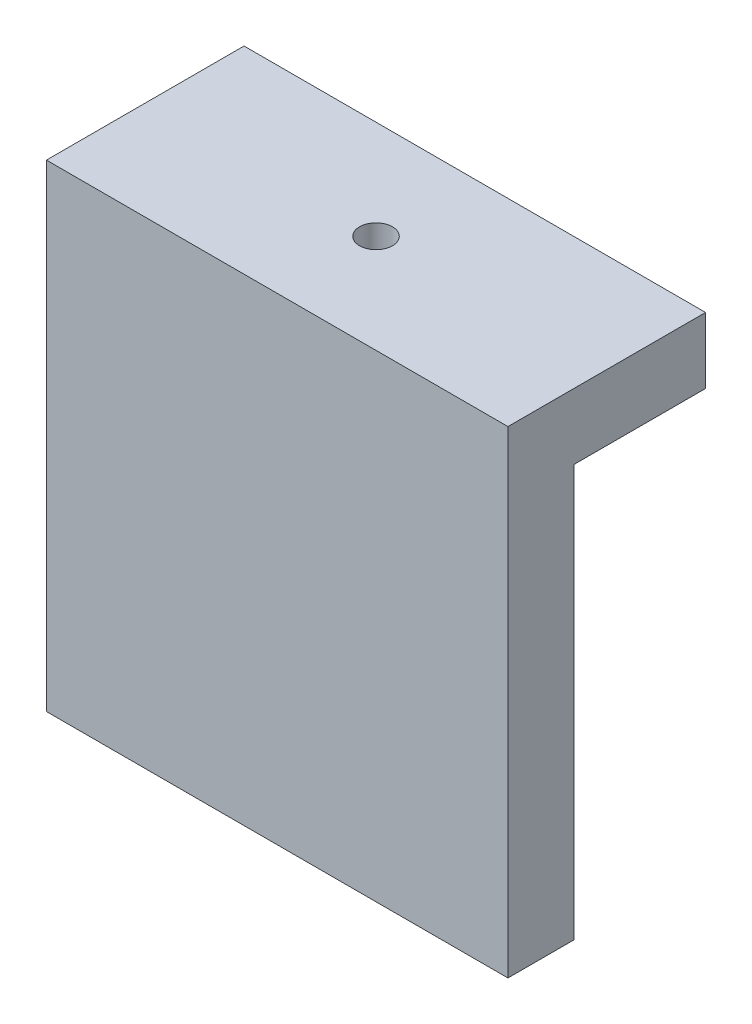
SolidWorks part; units mm, degrees
ref_plane "Front Plane" through (0, 0, 0) normal (0, 0, 1) x (1, 0, 0)
ref_plane "Top Plane" through (0, 0, 0) normal (0, 1, 0) x (1, 0, 0)
ref_plane "Right Plane" through (0, 0, 0) normal (1, 0, 0) x (0, 0, -1)
sketch "Sketch1" plane through (0, 0, 0) normal (0, 0, 1) x (1, 0, 0)
  line L1 (20.025, -25) -> (-20.025, -25)
  line L2 (20.025, -25) -> (20.025, 25)
  line L3 (20.025, 25) -> (-20.025, 25)
  line L4 (-20.025, -25) -> (-20.025, 25)
  line L5 (20.025, -25) -> (-20.025, 25) construction
  line L6 (20.025, 25) -> (-20.025, -25) construction
  point P0 (0, 0)
  dimension "D1" = 40.05
  dimension "D2" = 50
extrude "Boss-Extrude1" add sketch "Sketch1" along normal mid plane 8
sketch "Sketch2" plane through (20.025, 0, 0) normal (1, 0, 0) x (0, 0, -1)
  line L0 (-4, -25) -> (-4, 33)
  line L1 (-4, 33) -> (20, 33)
  line L2 (20, 33) -> (20, -25)
  line L3 (20, -25) -> (-4, -25)
  line L4 (4, -25) -> (4, 25) construction
  line L5 (-4, 25) -> (4, 25) construction
  dimension "D1" = 16
  dimension "D2" = 8
extrude "Boss-Extrude2" add sketch "Sketch2" along normal blind 8
sketch "Sketch4" plane through (-20.025, 0, 0) normal (-1, 0, 0) x (0, 0, 1)
  line L0 (4, -25) -> (-20, -25)
  line L1 (-20, -25) -> (-20, 33)
  line L2 (4, -25) -> (4, 33)
  line L3 (4, 33) -> (-20, 33)
  line L4 (-4, 25) -> (-4, -25) construction
  line L5 (4, 25) -> (-4, 25) construction
  dimension "D1" = 16
  dimension "D2" = 8
extrude "Boss-Extrude3" add sketch "Sketch4" along normal blind 8
sketch "Sketch5" plane through (20.025, 0, 0) normal (-1, 0, 0) x (0, 0, 1)
  line L0 (-20, -25) -> (-20, 33)
  line L1 (-20, 33) -> (4, 33)
  line L2 (4, 33) -> (4, 25)
  line L3 (4, 25) -> (-12.05, 25)
  line L4 (-12.05, 25) -> (-12.05, -25)
  line L5 (-4, -25) -> (-20, -25) construction
  line L6 (-12.05, -25) -> (-20, -25)
  dimension "D1" = 7.95
extrude "Boss-Extrude5" add sketch "Sketch5" along normal up to surface (40.05 mm away) from surface at 0 contours L6 L0 L1 L2 L3 L4 up to face at (-20.025, 11, -6.6667) starting at face at (20.025, 11, -6.6667)
sketch "Sketch6" plane through (0, 0, -20) normal (0, 0, -1) x (-1, 0, 0)
  line L0 (-16.025, -25) -> (-16.025, 25)
  line L1 (-28.025, -25) -> (28.025, -25) construction
  line L2 (-16.025, 25) -> (16.025, 25)
  line L3 (16.025, 25) -> (16.025, -25)
  line L4 (-28.025, -25) -> (-28.025, 33) construction
  line L5 (28.025, 33) -> (28.025, -25) construction
  line L6 (16.025, -25) -> (-16.025, -25)
  dimension "D1" = 12
  dimension "D2" = 12
  dimension "D3" = 50
extrude "Cut-Extrude1" cut sketch "Sketch6" against normal blind 8
sketch "Sketch7" plane through (0, 33, 0) normal (0, 1, 0) x (1, 0, 0)
  line L0 (28.025, 8) -> (-28.025, 8) construction
  line L1 (28.025, 20) -> (28.025, -4) construction
  line L2 (-28.025, -4) -> (-28.025, 20) construction
  line L3 (0, 20) -> (0, -4) construction
  line L4 (28.025, 20) -> (-28.025, 20) construction
  line L5 (28.025, -4) -> (-28.025, -4) construction
  circle A0 centre (0, 8) radius 2
  dimension "D1" = 4
extrude "Cut-Extrude2" cut sketch "Sketch7" against normal blind 8
sketch "Sketch9" plane through (20.025, 0, 0) normal (-1, 0, 0) x (0, 0, 1)
  line L0 (-8.025, -25) -> (-8.025, 25) construction
  line L1 (-4, -25) -> (-12.05, -25) construction
  line L2 (-12.05, 25) -> (-4, 25) construction
  line L4 (-4, -25) -> (-4, 25) construction
  line L6 (-4, 0) -> (-12.05, 0) construction
  circle A0 centre (-8.025, 0) radius 2
  dimension "D3" = 4
  dimension "D1" = 25
  dimension "D2" = 8.05
extrude "Cut-Extrude3" cut sketch "Sketch9" against normal mid plane 100
sketch "Sketch11" plane through (28.025, 0, 0) normal (1, 0, 0) x (0, 0, -1)
  line L0 (4, -25) -> (4, 25)
  line L1 (-4, -25) -> (20, -25) construction
  line L2 (4, 25) -> (20, 25)
  line L3 (20, -25) -> (20, 33) construction
  line L4 (20, 25) -> (20, -25)
  line L5 (20, -25) -> (4, -25)
  dimension "D1" = 50
  dimension "D2" = 16
extrude "Cut-Extrude4" cut sketch "Sketch11" against normal blind 80
